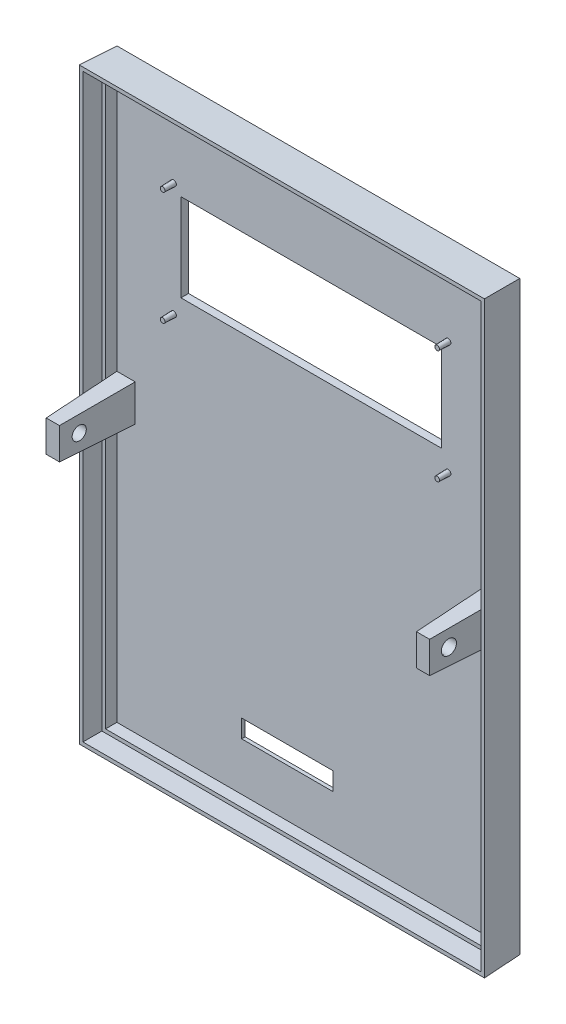
SolidWorks part; units mm, degrees
ref_plane "Front Plane" through (0, 0, 0) normal (0, 0, 1) x (1, 0, 0)
ref_plane "Top Plane" through (0, 0, 0) normal (0, 1, 0) x (1, 0, 0)
ref_plane "Right Plane" through (0, 0, 0) normal (1, 0, 0) x (0, 0, -1)
sketch "Sketch1" plane through (0, 0, 0) normal (0, 0, 1) x (1, 0, 0)
  line L1 (55, -80) -> (-55, -80)
  line L2 (55, -80) -> (55, 80)
  line L3 (55, 80) -> (-55, 80)
  line L4 (-55, -80) -> (-55, 80)
  line L5 (55, -80) -> (-55, 80) construction
  line L6 (55, 80) -> (-55, -80) construction
  point P0 (0, 0)
  dimension "D1" = 110
  dimension "D2" = 160
extrude "Boss-Extrude1" add sketch "Sketch1" along normal blind 10 draft 2 draft outward yes
shell "Shell1" thickness 2
sketch "Sketch3" plane through (0, 0, 10) normal (0, 0, 1) x (1, 0, 0)
  line L14 (54.3492, -79.3492) -> (54.3492, 79.3492)
  line L15 (-54.3492, -79.3492) -> (54.3492, -79.3492)
  line L16 (-54.3492, 79.3492) -> (-54.3492, -79.3492)
  line L17 (54.3492, 79.3492) -> (-54.3492, 79.3492)
  line L18 (54.3492, -79.3492) -> (54.3492, 79.3492)
  line L19 (-54.3492, -79.3492) -> (54.3492, -79.3492)
  line L20 (-54.3492, 79.3492) -> (-54.3492, -79.3492)
  line L21 (54.3492, 79.3492) -> (-54.3492, 79.3492)
  dimension "D1" = 1
extrude "Cut-Extrude3" cut sketch "Sketch3" against normal blind 5 draft 2
sketch "Sketch4" plane through (0, 0, 0) normal (0, 0, -1) x (-1, 0, 0)
  line L0 (-55, 80) -> (55, 80) construction
  line L1 (35.5, 31.2) -> (-35.5, 31.2)
  line L2 (35.5, 31.2) -> (35.5, 55)
  line L3 (35.5, 55) -> (-35.5, 55)
  line L4 (-35.5, 31.2) -> (-35.5, 55)
  line L5 (35.5, 31.2) -> (-35.5, 55) construction
  line L6 (35.5, 55) -> (-35.5, 31.2) construction
  line L7 (-55, -80) -> (-55, 80) construction
  point P0 (0, 43.1)
  dimension "D1" = 25
  dimension "D2" = 23.8
  dimension "D3" = 55
  dimension "D4" = 71
extrude "Cut-Extrude4" cut sketch "Sketch4" against normal up to next (2 mm away) draft 2 draft outward yes
sketch "Sketch9" plane through (0, 0, 2) normal (0, 0, 1) x (1, 0, 0)
  line L0 (-35.5698, 31.1302) -> (-35.5698, 55.0698) construction
  line L1 (39.9302, 25.1698) -> (-40.0698, 25.1698)
  line L2 (39.9302, 25.1698) -> (39.9302, 61.1698)
  line L3 (39.9302, 61.1698) -> (-40.0698, 61.1698)
  line L4 (-40.0698, 25.1698) -> (-40.0698, 61.1698)
  line L5 (39.9302, 25.1698) -> (-40.0698, 61.1698) construction
  line L6 (39.9302, 61.1698) -> (-40.0698, 25.1698) construction
  line L7 (-35.5698, 55.0698) -> (35.5698, 55.0698) construction
  point P0 (-0.0698, 43.1698)
  dimension "D1" = 80
  dimension "D2" = 36
  dimension "D3" = 35.5
  dimension "D4" = 11.9
sketch "Sketch10" plane through (0, 0, 2) normal (0, 0, 1) x (1, 0, 0)
  line L0 (39.9302, 25.1698) -> (-40.0698, 61.1698) construction
  line L1 (39.9302, 61.1698) -> (-40.0698, 25.1698) construction
  line L2 (-37.5698, 57.2948) -> (-37.5698, 26.2948) construction
  line L3 (-37.5698, 57.2948) -> (37.4302, 57.2948) construction
  line L4 (37.4302, 57.2948) -> (37.4302, 26.2948) construction
  line L5 (37.4302, 26.2948) -> (-37.5698, 26.2948) construction
  circle A0 centre (-37.5698, 57.2948) radius 0.75
  circle A1 centre (37.4302, 57.2948) radius 0.75
  circle A2 centre (37.4302, 26.2948) radius 0.75
  circle A3 centre (-37.5698, 26.2948) radius 0.75
  dimension "D3" = 1.5
  dimension "D4" = 1.5
  dimension "D5" = 1.5
  dimension "D6" = 1.5
  dimension "D1" = 75
  dimension "D2" = 31
extrude "Boss-Extrude3" add sketch "Sketch10" along normal blind 3 draft 2
sketch "Sketch13" plane through (0, 0, 2) normal (0, 0, 1) x (1, 0, 0)
  line L0 (-53.0686, 78.0686) -> (-53.0686, -78.0686) construction
  line L1 (-48.0686, 5) -> (-53.0686, 5)
  line L2 (-48.0686, 5) -> (-48.0686, -5)
  line L3 (-48.0686, -5) -> (-53.0686, -5)
  line L4 (-53.0686, 5) -> (-53.0686, -5)
  line L5 (-48.0686, 5) -> (-53.0686, -5) construction
  line L6 (-48.0686, -5) -> (-53.0686, 5) construction
  line L7 (53.0686, -78.0686) -> (53.0686, 78.0686) construction
  line L8 (48.0686, -5) -> (53.0686, -5)
  line L9 (48.0686, -5) -> (48.0686, 5)
  line L10 (48.0686, 5) -> (53.0686, 5)
  line L11 (53.0686, -5) -> (53.0686, 5)
  line L12 (48.0686, -5) -> (53.0686, 5) construction
  line L13 (48.0686, 5) -> (53.0686, -5) construction
  point P0 (-50.5686, 0)
  point P8 (50.5686, 0)
  dimension "D1" = 10
  dimension "D2" = 5
  dimension "D3" = 0
  dimension "D4" = 0
  dimension "D5" = 10
  dimension "D6" = 0
  dimension "D7" = 0
  dimension "D8" = 5
extrude "Boss-Extrude8" add sketch "Sketch13" along normal blind 20 draft 2
sketch "Sketch21" plane through (-53.0737, 0, 1.8534) normal (-0.9994, 0, 0.0349) x (0.0349, 0, 0.9994)
  line L0 (8.0622, 80.3492) -> (8.0622, -80.3492) construction
  circle A0 centre (15.0622, 0) radius 2
  dimension "D1" = 4
  dimension "D2" = 7
  dimension "D3" = 4.3016
extrude "Cut-Extrude8" cut sketch "Sketch21" against normal up to next draft 2
sketch "Sketch22" plane through (53.0737, 0, 1.8534) normal (0.9994, 0, 0.0349) x (0.0349, 0, -0.9994)
  line L0 (-8.0622, -80.3492) -> (-8.0622, 80.3492) construction
  circle A0 centre (-15.0622, 0) radius 2
  dimension "D1" = 4
  dimension "D2" = 7
  dimension "D3" = 4.3016
extrude "Cut-Extrude9" cut sketch "Sketch22" against normal up to next draft 2
sketch "Sketch27" plane through (0, 0, 0) normal (0, 0, -1) x (-1, 0, 0)
  line L0 (55, 80) -> (55, -80) construction
  line L1 (40, -69.8) -> (-29, -69.8)
  line L2 (40, -69.8) -> (40, 6.2)
  line L3 (40, 6.2) -> (-29, 6.2)
  line L4 (-29, -69.8) -> (-29, 6.2)
  line L5 (40, -69.8) -> (-29, 6.2) construction
  line L6 (40, 6.2) -> (-29, -69.8) construction
  line L7 (55, -80) -> (-55, -80) construction
  point P0 (5.5, -31.8)
  dimension "D1" = 69
  dimension "D2" = 76
  dimension "D3" = 15
  dimension "D4" = 10.2
extrude "Cut-Extrude10" cut sketch "Sketch27" against normal blind 1 draft 2
sketch "Sketch28" plane through (0, 0, 1) normal (0, 0, -1) x (-1, 0, 0)
  line L0 (-28.9651, -69.7651) -> (39.9651, -69.7651) construction
  line L1 (19.0349, -59.9651) -> (-5.9651, -59.9651)
  line L2 (19.0349, -59.9651) -> (19.0349, -64.9651)
  line L3 (19.0349, -64.9651) -> (-5.9651, -64.9651)
  line L4 (-5.9651, -59.9651) -> (-5.9651, -64.9651)
  line L5 (19.0349, -59.9651) -> (-5.9651, -64.9651) construction
  line L6 (19.0349, -64.9651) -> (-5.9651, -59.9651) construction
  line L7 (-28.9651, 6.1651) -> (-28.9651, -69.7651) construction
  point P0 (6.5349, -62.4651)
  dimension "D1" = 4.8
  dimension "D2" = 5
  dimension "D3" = 25
  dimension "D4" = 23
extrude "Cut-Extrude11" cut sketch "Sketch28" against normal up to next (1 mm away) draft 2
